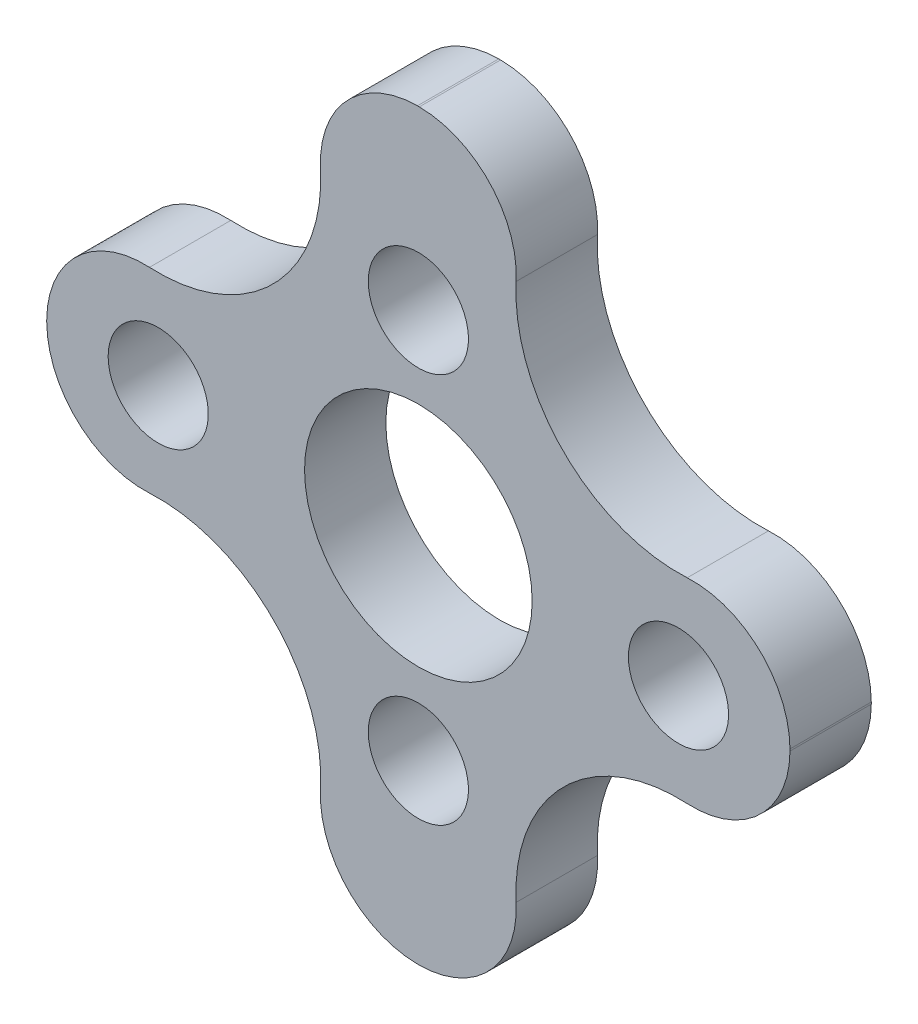
SolidWorks part; units mm, degrees
ref_plane "前视基准面" through (0, 0, 0) normal (0, 0, 1) x (1, 0, 0)
ref_plane "上视基准面" through (0, 0, 0) normal (0, 1, 0) x (1, 0, 0)
ref_plane "右视基准面" through (0, 0, 0) normal (1, 0, 0) x (0, 0, -1)
sketch "草图1" plane through (0, 0, 0) normal (0, 0, 1) x (1, 0, 0)
  line L4 (0, -13.5) -> (0, 13.5) construction
  line L5 (-13.5, 0) -> (13.5, 0) construction
  line L6 (0, 13.5) -> (13.5, 0)
  line L7 (13.5, 0) -> (0, -13.5)
  line L8 (0, -13.5) -> (-13.5, 0)
  line L9 (-13.5, 0) -> (0, 13.5)
extrude "凸台-拉伸1" add sketch "草图1" along normal blind 2.5
fillet "圆角1" radius 5 1 edges at (13.5, 0, 1.25)
fillet "圆角2" radius 5 1 edges at (0, -13.5, 1.25)
fillet "圆角3" radius 5 1 edges at (-13.5, 0, 1.25)
fillet "圆角4" radius 5 1 edges at (0, 13.5, 1.25)
sketch "草图2" plane through (0, 0, 0) normal (0, 0, -1) x (-1, 0, 0)
  circle A0 centre (0, 0) radius 3.5
  circle A1 centre (0, -6) radius 1.54
  circle A2 centre (0, 6) radius 1.54
  circle A3 centre (8, 0) radius 1.54
  circle A4 centre (-8, 0) radius 1.54
  circle A5 centre (8, 8) radius 5
  circle A6 centre (8, -8) radius 5
  circle A7 centre (-8, -8) radius 5
  circle A8 centre (-8, 8) radius 5
  point P22 (0, 0)
  dimension "D1" = 4
extrude "切除-拉伸2" cut sketch "草图2" against normal blind 2.5
fillet "圆角5" radius 3 1 edges at (3.4421, -10.0555, 1.25)
fillet "圆角6" radius 3 1 edges at (-3.4421, -10.0555, 1.25)
fillet "圆角7" radius 3 1 edges at (-10.0555, -3.4421, 1.25)
fillet "圆角8" radius 3 1 edges at (3.4421, 10.0555, 1.25)
fillet "圆角9" radius 3 1 edges at (-3.4421, 10.0555, 1.25)
fillet "圆角10" radius 3 1 edges at (-10.0555, 3.4421, 1.25)
fillet "圆角11" radius 3 1 edges at (10.0555, -3.4421, 1.25)
fillet "圆角12" radius 3 1 edges at (10.0555, 3.4421, 1.25)
